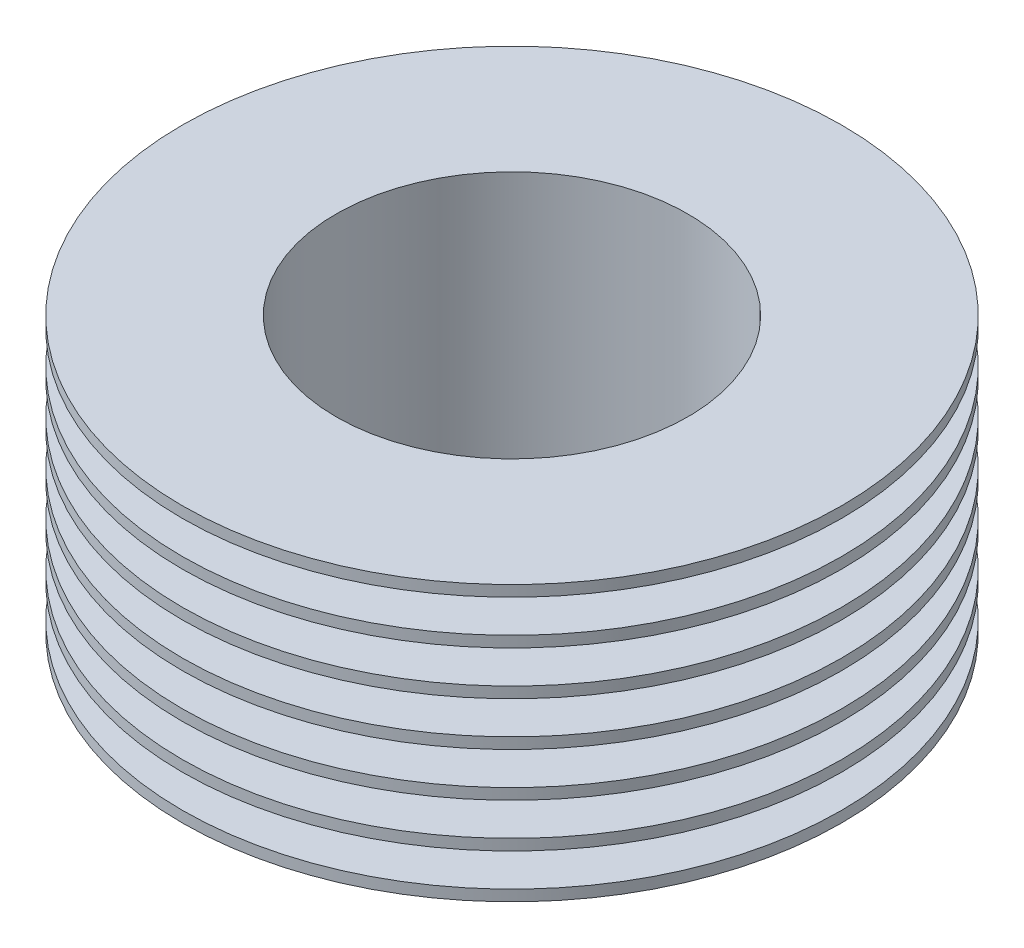
SolidWorks part; units mm, degrees
ref_plane "Front Plane" through (0, 0, 0) normal (0, 0, 1) x (1, 0, 0)
ref_plane "Top Plane" through (0, 0, 0) normal (0, 1, 0) x (1, 0, 0)
ref_plane "Right Plane" through (0, 0, 0) normal (1, 0, 0) x (0, 0, -1)
sketch "Sketch1" plane through (0, 0, 0) normal (1, 0, 0) x (0, 0, -1)
  line L0 (0, 28.0586) -> (0, -24.3494) construction
  line L4 (-18, 14.8387) -> (-18, 9.8387)
  line L5 (-18, 9.8387) -> (-30, 9.8387)
  line L6 (-30, 9.8387) -> (-30, 8.8387)
  line L7 (-30, 8.8387) -> (-16, 8.8387)
  line L8 (-16, 8.8387) -> (-16, 14.8387)
  line L11 (-18, 14.8387) -> (-16, 14.8387)
  dimension "D1" = 6
  dimension "D2" = 32
  dimension "D4" = 36
  dimension "D5" = 1
  dimension "D7" = 60
revolve "Revolve1" add sketch "Sketch1" angle 360 about L0
pattern_linear "LPattern1" count 7 spacing 4 along (0, 1, 0) of "Revolve1"
sketch "Sketch3" plane through (0, 38.8387, 0) normal (0, 1, 0) x (1, 0, 0)
  circle A0 centre (0, 0) radius 19.0474
extrude "Cut-Extrude3" cut sketch "Sketch3" against normal up to surface (5 mm away) up to face at (0, 33.8387, 30)
